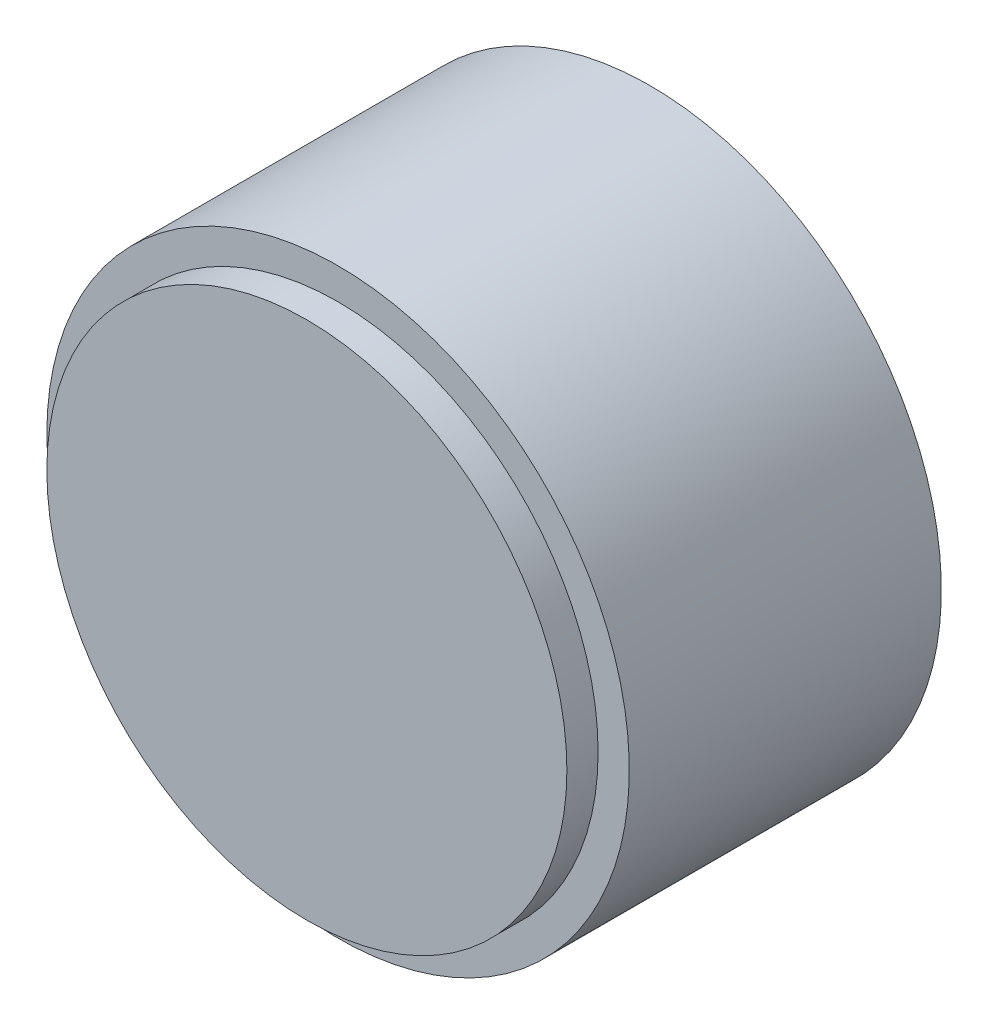
SolidWorks part; units mm, degrees
ref_plane "Plan de face" through (0, 0, 0) normal (0, 0, 1) x (1, 0, 0)
ref_plane "Plan de dessus" through (0, 0, 0) normal (0, 1, 0) x (1, 0, 0)
ref_plane "Plan de droite" through (0, 0, 0) normal (1, 0, 0) x (0, 0, -1)
sketch "Esquisse1" plane through (0, 0, 0) normal (0, 0, 1) x (1, 0, 0)
  circle A0 centre (0, 0) radius 25
  point P14 (0, 0)
  dimension "D1" = 50
extrude "Boss.-Extru.1" add sketch "Esquisse1" along normal blind 35
sketch "Esquisse3" plane through (0, 0, 0) normal (0, 0, -1) x (-1, 0, 0)
  circle A2 centre (0, 0) radius 25 construction
  circle A3 centre (0, 0) radius 28
  circle A4 centre (0, 0) radius 28
  circle A5 centre (0, 0) radius 25
  dimension "D1" = 3
extrude "Boss.-Extru.2" add sketch "Esquisse3" against normal blind 30 from offset 2 offset against normal yes
sketch "Esquisse4" plane through (0, 0, 0) normal (0, 0, -1) x (-1, 0, 0)
  circle A0 centre (0, 0) radius 2
  circle A2 centre (0, 0) radius 7
  dimension "D1" = 4
  dimension "D2" = 5
extrude "Boss.-Extru.3" add sketch "Esquisse4" along normal blind 5
sketch "Esquisse5" plane through (0, 0, 0) normal (0, 1, 0) x (1, 0, 0)
  line L0 (2, 5) -> (-2, 5) construction
  line L1 (2, 5) -> (-2, 5)
  line L2 (25, 0) -> (-25, 0) construction
  line L3 (25, 0) -> (-25, 0)
  line L4 (-7, 5) -> (-7, 0) construction
  line L5 (-7, 5) -> (-7, 0)
  circle A0 centre (0, 2.5) radius 1.5
  point P10 (-7, 2.5)
  dimension "D1" = 3
extrude "Enlèv. mat.-Extru.1" cut sketch "Esquisse5" along normal through all contours A0
